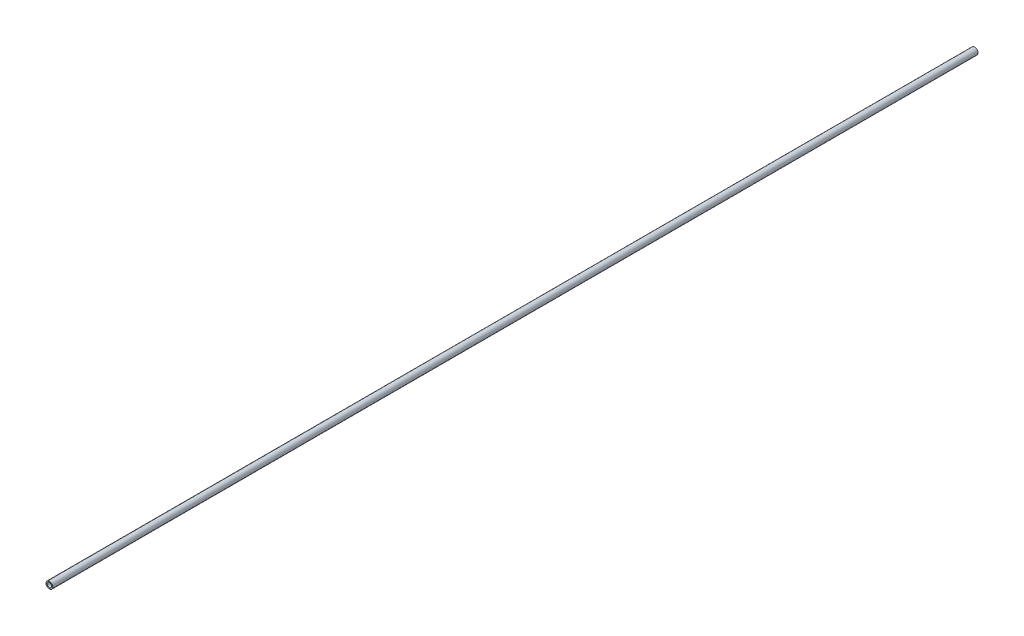
SolidWorks part; units mm, degrees
material "Carbon Fiber Tube - UD Approx"
ref_plane "Front Plane" through (0, 0, 0) normal (0, 0, 1) x (1, 0, 0)
ref_plane "Top Plane" through (0, 0, 0) normal (0, 1, 0) x (1, 0, 0)
ref_plane "Right Plane" through (0, 0, 0) normal (1, 0, 0) x (0, 0, -1)
sketch "Sketch1" plane through (0, 0, 0) normal (0, 0, 1) x (1, 0, 0)
  circle A0 centre (0, 0) radius 3
  circle A1 centre (0, 0) radius 2
  dimension "D1" = 6
  dimension "D2" = 4
extrude "Boss-Extrude1" add sketch "Sketch1" along normal blind 820
